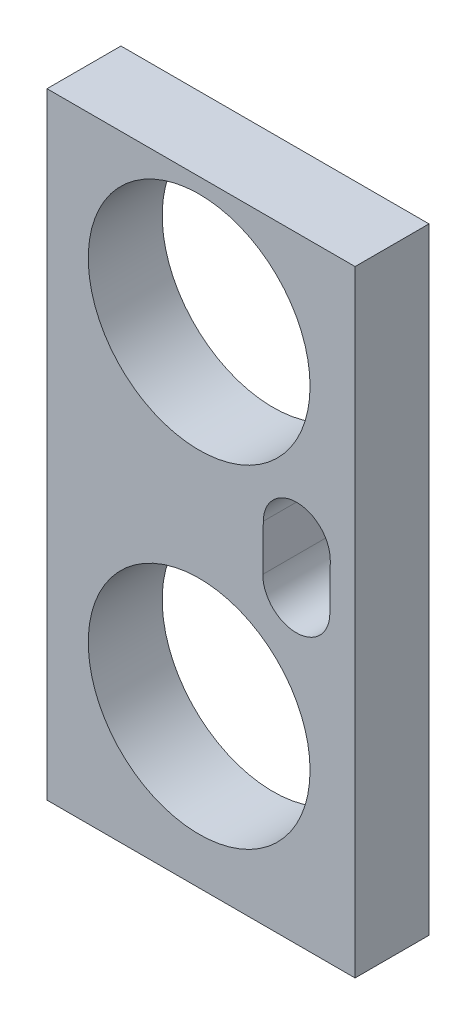
SolidWorks part; units mm, degrees
ref_plane "Front Plane" through (0, 0, 0) normal (0, 0, 1) x (1, 0, 0)
ref_plane "Top Plane" through (0, 0, 0) normal (0, 1, 0) x (1, 0, 0)
ref_plane "Right Plane" through (0, 0, 0) normal (1, 0, 0) x (0, 0, -1)
sketch "Sketch1" plane through (0, 0, 0) normal (0, 0, 1) x (1, 0, 0)
  line L1 (-15.7895, 18.6404) -> (9.2105, 18.6404)
  line L2 (-15.7895, 18.6404) -> (-15.7895, -31.3596)
  line L3 (-15.7895, -31.3596) -> (9.2105, -31.3596)
  line L4 (9.2105, 18.6404) -> (9.2105, -31.3596)
  dimension "D1" = 25
  dimension "D2" = 50
extrude "Boss-Extrude1" add sketch "Sketch1" along normal blind 6
sketch "Sketch2" plane through (0, 0, 6) normal (0, 0, 1) x (1, 0, 0)
  line L0 (29.4505, 26.3099) -> (29.4505, -39.9331) construction
  line L1 (26.7896, 25.6096) -> (26.7896, -40.0732) construction
  line L2 (28.19, 25.3295) -> (28.19, -40.3533) construction
  line L3 (4.4807, -3.0135) -> (4.4425, -6.7627) construction
  line L4 (7.1996, -3.0412) -> (7.1613, -6.7904)
  line L5 (1.7618, -2.9857) -> (1.7236, -6.7349)
  circle A0 centre (-3.4423, 8.4093) radius 9
  circle A1 centre (-3.4423, -18.5907) radius 9
  arc A2 (7.1996, -3.0412) -> (1.7618, -2.9857) centre (4.4807, -3.0135) ccw
  arc A3 (1.7236, -6.7349) -> (7.1613, -6.7904) centre (4.4425, -6.7627) ccw
  point P12 (4.4616, -4.8881)
  point P17 (0, 0)
  point P18 (0, 0)
  point P19 (0, 0)
  point P20 (0, 0)
  point P21 (7.3544, 9.6825)
  point P22 (0, 0)
  point P23 (0, 0)
  point P24 (0, 0)
  point P25 (0, 0)
  point P26 (0, 0)
  point P27 (-3.3913, 8.5621)
  point P28 (-3.2385, -18.5822)
  point P29 (0, 0)
  point P30 (0, 0)
  point P31 (-3.4423, 8.4093)
  point P32 (0, 0)
  point P33 (0, 0)
  point P34 (0, 0)
  point P35 (0, 0)
  point P36 (0, 0)
  dimension "D1" = 18
  dimension "D2" = 18
  dimension "D3" = 13.2974
  dimension "D4" = 27
extrude "Cut-Extrude1" cut sketch "Sketch2" against normal through all
